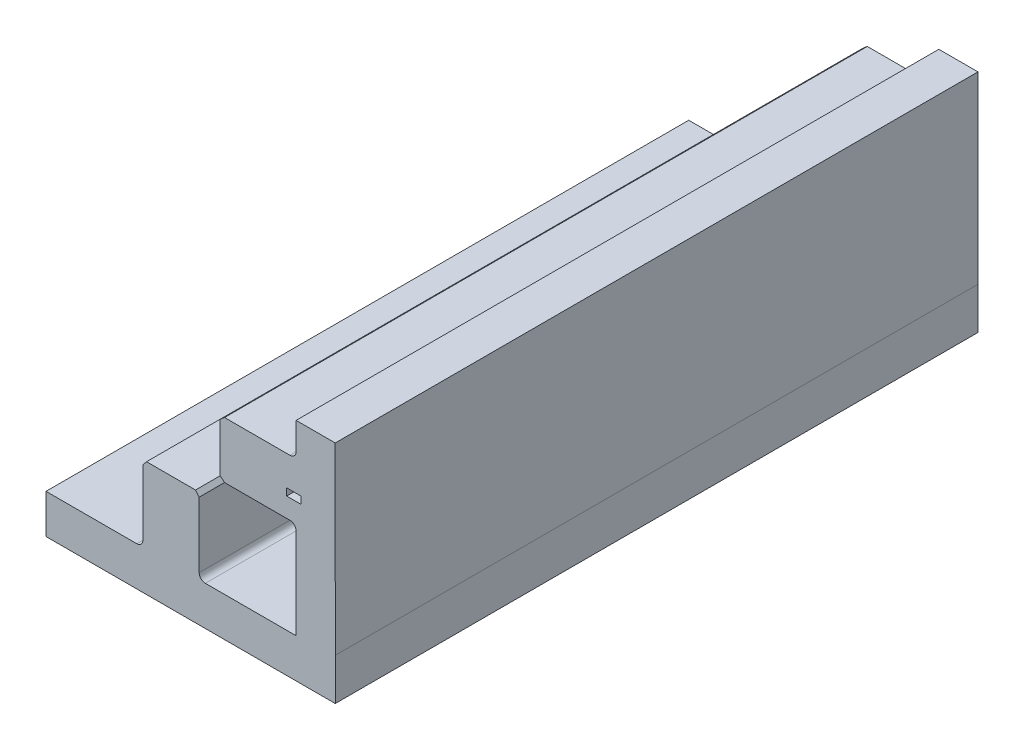
SolidWorks part; units mm, degrees
ref_plane "Front Plane" through (0, 0, 0) normal (0, 0, 1) x (1, 0, 0)
ref_plane "Top Plane" through (0, 0, 0) normal (0, 1, 0) x (1, 0, 0)
ref_plane "Right Plane" through (0, 0, 0) normal (1, 0, 0) x (0, 0, -1)
ref_plane "Plane1" through (0, 0, -3683) normal (0, 0, -1) x (-1, 0, 0)
sketch "Sketch1" plane through (0, 0, -3683) normal (0, 0, -1) x (-1, 0, 0)
  line L0 (7.9453, 3.5889) -> (-1.1987, 3.5889)
  line L1 (-1.8337, 4.2239) -> (-1.8337, 5.7479)
  line L2 (-1.1987, 6.3829) -> (1.6216, 6.3829)
  line L3 (1.6216, 6.3829) -> (1.6216, 6.8909)
  line L4 (1.6216, 6.8909) -> (-2.2147, 11.4629)
  line L5 (-2.2147, 11.4629) -> (-7.2947, 11.4629)
  line L6 (-7.2947, 11.4629) -> (-11.1311, 6.8909)
  line L7 (-11.1311, 6.8909) -> (-11.1311, 6.3829)
  line L8 (-11.1311, 6.3829) -> (-8.3107, 6.3829)
  line L9 (-7.6757, 5.7479) -> (-7.6757, 4.2239)
  line L10 (-8.3107, 3.5889) -> (-17.4547, 3.5889)
  line L11 (-17.7279, 3.8588) -> (-17.7284, 13.0024)
  line L12 (-17.4548, -0.4751) -> (7.9452, -0.4751)
  line L13 (-17.0929, 13.6378) -> (-15.5689, 13.6378)
  line L29 (-17.4547, 3.5889) -> (-17.7279, 3.5889)
  line L30 (-17.4548, -0.4751) -> (-17.7279, -0.4751)
  line L32 (8.2155, 3.5889) -> (8.2155, -0.4751)
  line L34 (8.2155, 3.5889) -> (7.9453, 3.5889)
  line L35 (8.2155, -0.4751) -> (7.9452, -0.4751)
  line L36 (-14.9339, 13.0028) -> (-14.9339, 10.1825)
  line L37 (-14.9339, 10.1825) -> (-14.4259, 10.1825)
  line L38 (-14.4259, 10.1825) -> (-9.8539, 14.0188)
  line L39 (-9.8539, 14.0188) -> (-9.8539, 19.0988)
  line L40 (-9.8539, 19.0988) -> (-14.4259, 22.9352)
  line L41 (-14.4259, 22.9352) -> (-14.9339, 22.9352)
  line L42 (-14.9339, 22.9352) -> (-14.9339, 20.1148)
  line L43 (-15.5689, 19.4798) -> (-17.0929, 19.4798)
  line L44 (-17.7287, 20.1156) -> (-17.7288, 22.9352)
  line L45 (-21.7872, 22.9352) -> (-21.7919, 3.8591)
  line L49 (-17.7288, 22.9352) -> (-21.7872, 22.9352)
  line L51 (-17.7279, 3.5889) -> (-17.7279, 3.8588)
  line L52 (-21.7919, 3.5889) -> (-21.7919, 3.8591)
  line L54 (-17.7279, -0.4751) -> (-21.7919, -0.4751)
  line L56 (-21.7919, -0.4751) -> (-21.7919, 3.5889)
  arc A0 (-1.1987, 3.5889) -> (-1.8337, 4.2239) centre (-1.1987, 4.2239) cw
  arc A1 (-1.8337, 5.7479) -> (-1.1987, 6.3829) centre (-1.1987, 5.7479) cw
  arc A2 (-8.3107, 6.3829) -> (-7.6757, 5.7479) centre (-8.3107, 5.7479) cw
  arc A3 (-7.6757, 4.2239) -> (-8.3107, 3.5889) centre (-8.3107, 4.2239) cw
  arc A4 (-17.7284, 13.0024) -> (-17.0929, 13.6378) centre (-17.0929, 13.0024) cw
  arc A5 (-15.5689, 13.6378) -> (-14.9339, 13.0028) centre (-15.5689, 13.0028) cw
  arc A6 (-14.9339, 20.1148) -> (-15.5689, 19.4798) centre (-15.5689, 20.1148) cw
  arc A7 (-17.0929, 19.4798) -> (-17.7287, 20.1156) centre (-17.0929, 20.1156) cw
extrude "Boss-Extrude1" add sketch "Sketch1" along normal blind 66.675
sketch "Sketch2" plane through (0, 0, -3683) normal (0, 0, 1) x (1, 0, 0)
  line L0 (11.1311, 6.8909) -> (11.1311, 6.3829) construction
  line L1 (11.1311, 6.3829) -> (8.3107, 6.3829) construction
  line L2 (7.2947, 11.4629) -> (11.1311, 6.8909) construction
  line L3 (4.7547, 11.4629) -> (4.7547, -3.7872) construction
  line L4 (7.6757, 5.7479) -> (7.6757, 4.2239) construction
  line L5 (11.1311, 6.8909) -> (11.1311, 6.3829)
  line L6 (11.1311, 6.3829) -> (8.3107, 6.3829)
  line L7 (7.6757, 11.0088) -> (11.1311, 6.8909)
  line L8 (2.2147, 11.4629) -> (7.2947, 11.4629) construction
  line L9 (7.6757, 5.7479) -> (7.6757, 11.0088)
  line L10 (1.8337, 5.7479) -> (1.8337, 11.0088)
  line L11 (1.8337, 11.0088) -> (-1.6216, 6.8909)
  line L12 (-1.6216, 6.3829) -> (1.1987, 6.3829)
  line L13 (-1.6216, 6.8909) -> (-1.6216, 6.3829)
  arc A0 (8.3107, 6.3829) -> (7.6757, 5.7479) centre (8.3107, 5.7479) ccw construction
  arc A1 (8.3107, 6.3829) -> (7.6757, 5.7479) centre (8.3107, 5.7479) ccw
  arc A2 (1.1987, 6.3829) -> (1.8337, 5.7479) centre (1.1987, 5.7479) cw
extrude "Cut-Extrude1" cut sketch "Sketch2" against normal up to next
sketch "Sketch3" plane through (0, 0, -3683) normal (0, 0, 1) x (1, 0, 0)
  line L0 (15.5689, 19.4798) -> (17.0929, 19.4798) construction
  line L1 (14.9339, 22.9352) -> (14.9339, 20.1148) construction
  line L2 (14.4259, 22.9352) -> (14.9339, 22.9352) construction
  line L3 (9.8539, 19.0988) -> (14.4259, 22.9352) construction
  line L4 (15.5689, 19.4798) -> (10.308, 19.4798)
  line L5 (14.9339, 22.9352) -> (14.9339, 20.1148)
  line L6 (14.4259, 22.9352) -> (14.9339, 22.9352)
  line L7 (10.308, 19.4798) -> (14.4259, 22.9352)
  line L8 (9.8539, 16.5588) -> (24.7491, 16.5588) construction
  line L9 (9.8539, 14.0188) -> (9.8539, 19.0988) construction
  line L10 (10.308, 13.6378) -> (14.4259, 10.1825)
  line L11 (14.4259, 10.1825) -> (14.9339, 10.1825)
  line L12 (14.9339, 10.1825) -> (14.9339, 13.0028)
  line L13 (15.5689, 13.6378) -> (10.308, 13.6378)
  arc A0 (14.9339, 20.1148) -> (15.5689, 19.4798) centre (15.5689, 20.1148) ccw construction
  arc A1 (14.9339, 20.1148) -> (15.5689, 19.4798) centre (15.5689, 20.1148) ccw
  arc A2 (14.9339, 13.0028) -> (15.5689, 13.6378) centre (15.5689, 13.0028) cw
extrude "Cut-Extrude2" cut sketch "Sketch3" against normal up to next
sketch "Sketch4" plane through (0, 0, -3683) normal (0, 0, 1) x (1, 0, 0)
  line L0 (2.2147, 11.4629) -> (7.2947, 11.4629) construction
  line L1 (9.8539, 14.0188) -> (9.8539, 19.0988) construction
  point P0 (4.7547, 11.4629)
  point P1 (9.8539, 16.5588)
sketch "Sketch5" plane through (0, 0, -3683) normal (0, 0, 1) x (1, 0, 0)
  line L1 (16.752, 16.386) -> (18.2413, 16.386)
  line L2 (16.752, 16.386) -> (16.752, 15.6466)
  line L3 (16.752, 15.6466) -> (18.2413, 15.6466)
  line L4 (18.2413, 16.386) -> (18.2413, 15.6466)
extrude "Cut-Extrude3" cut sketch "Sketch5" against normal blind 2.54
